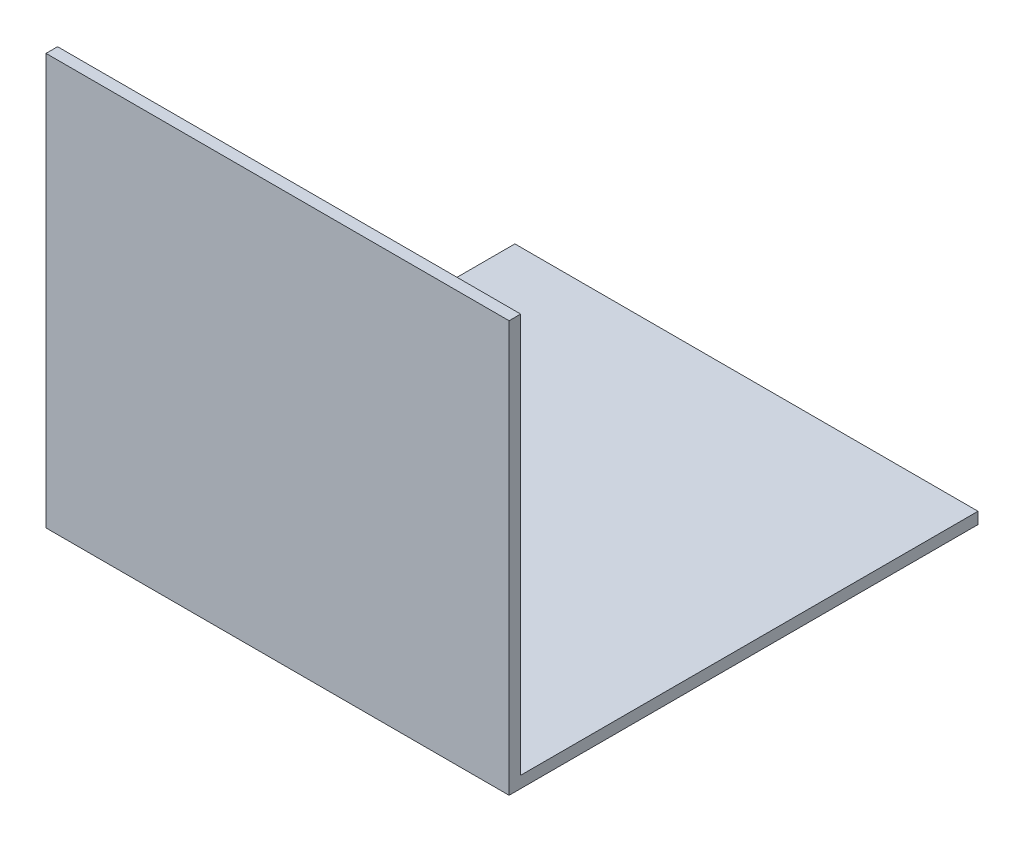
SolidWorks part; units mm, degrees
ref_plane "Front Plane" through (0, 0, 0) normal (0, 0, 1) x (1, 0, 0)
ref_plane "Top Plane" through (0, 0, 0) normal (0, 1, 0) x (1, 0, 0)
ref_plane "Right Plane" through (0, 0, 0) normal (1, 0, 0) x (0, 0, -1)
sketch "Sketch2" plane through (0, 0, 0) normal (1, 0, 0) x (0, 0, -1)
  line L0 (0, 700) -> (0, 0)
  line L1 (0, 0) -> (800, 0)
  dimension "D1" = 700
  dimension "D2" = 800
extrude "Extrude-Thin1" add sketch "Sketch2" along normal blind 800 thin thin type mid plane wall 20
